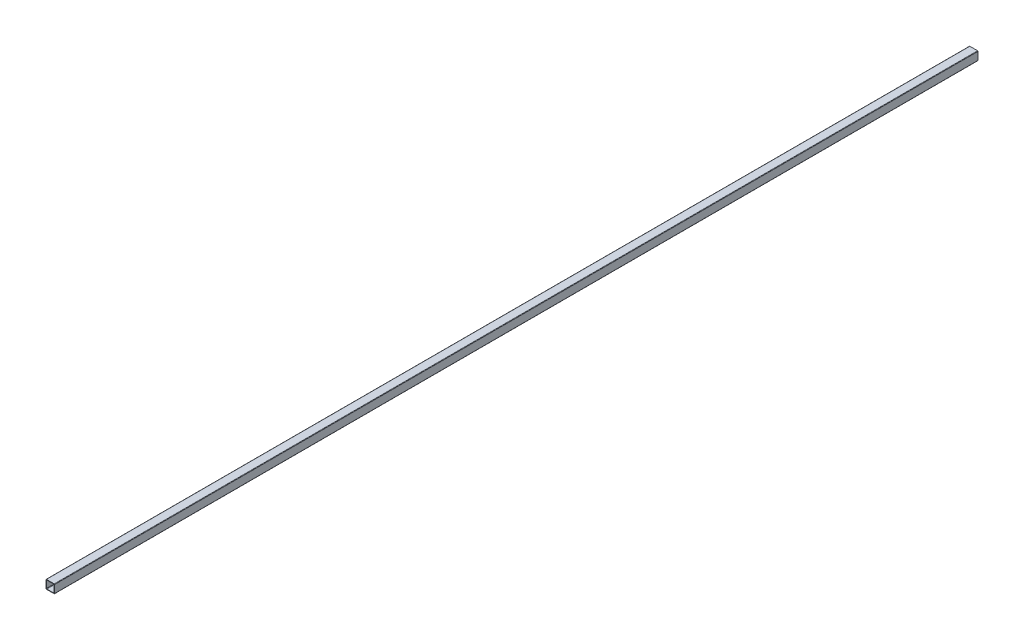
SolidWorks part; units mm, degrees
ref_plane "Спереди" through (0, 0, 0) normal (0, 0, 1) x (1, 0, 0)
ref_plane "Сверху" through (0, 0, 0) normal (0, 1, 0) x (1, 0, 0)
ref_plane "Справа" through (0, 0, 0) normal (1, 0, 0) x (0, 0, -1)
sketch "Эскиз1" plane through (0, 0, 0) normal (0, 0, 1) x (1, 0, 0)
  line L1 (18, -20) -> (-18, -20)
  line L2 (20, -18) -> (20, 18)
  line L3 (18, 20) -> (-18, 20)
  line L4 (-20, -18) -> (-20, 18)
  line L5 (20, -20) -> (-20, 20) construction
  line L6 (20, 20) -> (-20, -20) construction
  line L7 (16, -18) -> (-16, -18)
  line L8 (18, -16) -> (18, 16)
  line L9 (16, 18) -> (-16, 18)
  line L10 (-18, -16) -> (-18, 16)
  line L11 (18, -18) -> (-18, 18) construction
  line L12 (18, 18) -> (-18, -18) construction
  arc A0 (20, 18) -> (18, 20) centre (18, 18) ccw
  arc A1 (18, 16) -> (16, 18) centre (16, 16) ccw
  arc A2 (18, -20) -> (20, -18) centre (18, -18) ccw
  arc A3 (16, -18) -> (18, -16) centre (16, -16) ccw
  arc A4 (-18, -20) -> (-20, -18) centre (-18, -18) cw
  arc A5 (-16, -18) -> (-18, -16) centre (-16, -16) cw
  arc A6 (-18, 20) -> (-20, 18) centre (-18, 18) ccw
  arc A7 (-16, 18) -> (-18, 16) centre (-16, 16) ccw
  point P0 (0, 0)
  point P6 (0, 0)
  dimension "D5" = 2
  dimension "D1" = 40
  dimension "D2" = 40
  dimension "D3" = 2
  dimension "D4" = 2
extrude "Бобышка-Вытянуть1" add sketch "Эскиз1" along normal blind 4300
